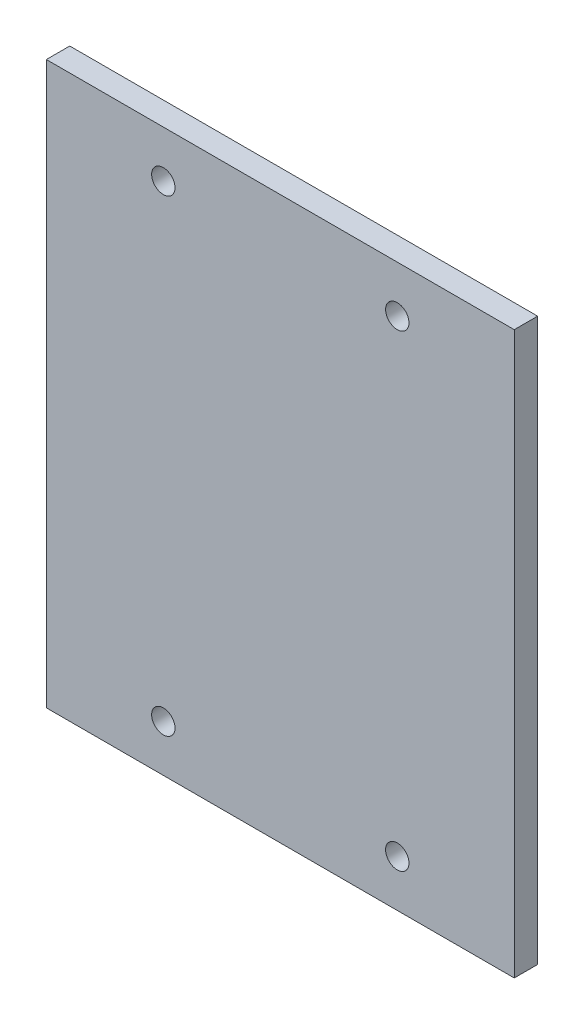
SolidWorks part; units mm, degrees
material "6061-T6 (SS)"
ref_plane "Front" through (0, 0, 0) normal (0, 0, 1) x (1, 0, 0)
ref_plane "Top" through (0, 0, 0) normal (0, 1, 0) x (1, 0, 0)
ref_plane "Right" through (0, 0, 0) normal (1, 0, 0) x (0, 0, -1)
sketch "Sketch1" plane through (0, 0, 0) normal (0, 0, 1) x (1, 0, 0)
  line L1 (-63.5, -76.2) -> (63.5, -76.2)
  line L2 (-63.5, -76.2) -> (-63.5, 76.2)
  line L3 (-63.5, 76.2) -> (63.5, 76.2)
  line L4 (63.5, -76.2) -> (63.5, 76.2)
  line L5 (-63.5, -76.2) -> (63.5, 76.2) construction
  line L6 (-63.5, 76.2) -> (63.5, -76.2) construction
  line L7 (-31.75, -63.5) -> (31.75, -63.5) construction
  line L8 (-31.75, -63.5) -> (-31.75, 63.5) construction
  line L9 (-31.75, 63.5) -> (31.75, 63.5) construction
  line L10 (31.75, -63.5) -> (31.75, 63.5) construction
  line L11 (-31.75, -63.5) -> (31.75, 63.5) construction
  line L12 (-31.75, 63.5) -> (31.75, -63.5) construction
  circle A0 centre (-31.75, -63.5) radius 3.175
  circle A1 centre (31.75, -63.5) radius 3.175
  circle A2 centre (31.75, 63.5) radius 3.175
  circle A3 centre (-31.75, 63.5) radius 3.175
  point P0 (0, 0)
  point P6 (31.9972, -63.5)
  point P10 (0, 0)
  point P12 (-30.7104, 63.5)
  point P14 (-31.4904, -63.5)
  point P19 (32.1815, 63.5)
  dimension "D3" = 6.35
  dimension "D4" = 6.35
  dimension "D5" = 63.5
  dimension "D7" = 6.35
  dimension "D8" = 6.35
  dimension "D1" = 152.4
  dimension "D2" = 127
  dimension "D6" = 127
extrude "Boss-Extrude1" add sketch "Sketch1" along normal blind 6.35
